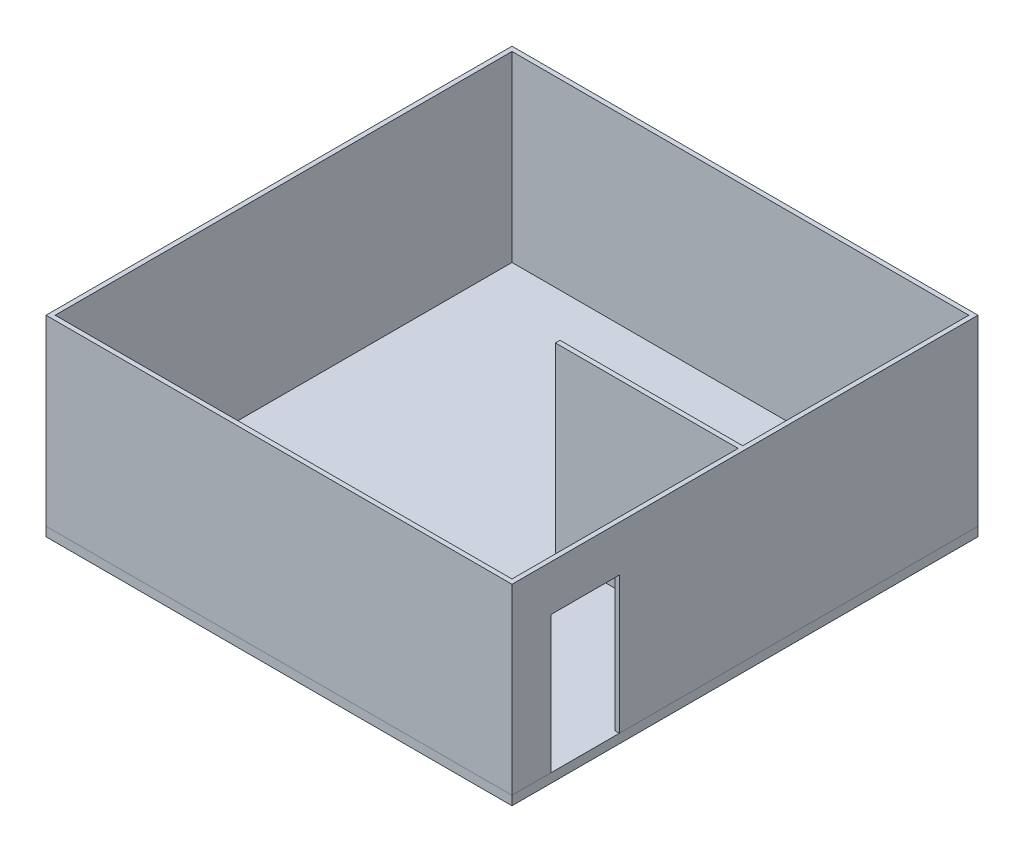
SolidWorks part; units mm, degrees
ref_plane "Front Plane" through (0, 0, 0) normal (0, 0, 1) x (1, 0, 0)
ref_plane "Top Plane" through (0, 0, 0) normal (0, 1, 0) x (1, 0, 0)
ref_plane "Right Plane" through (0, 0, 0) normal (1, 0, 0) x (0, 0, -1)
sketch "Sketch1" plane through (0, 0, 0) normal (0, 1, 0) x (1, 0, 0)
  line L0 (-5100, 5100) -> (-5100, -5100)
  line L1 (-5000, 5000) -> (5000, 5000)
  line L2 (-5000, 5000) -> (-5000, -5000)
  line L3 (-5000, -5000) -> (5000, -5000)
  line L4 (5000, 5000) -> (5000, -5000)
  line L5 (-5000, 5000) -> (5000, -5000) construction
  line L6 (-5000, -5000) -> (5000, 5000) construction
  line L7 (-5100, -5100) -> (5100, -5100)
  line L8 (5100, 5100) -> (5100, -5100)
  line L9 (-5100, 5100) -> (5100, 5100)
  line L11 (5000, 50) -> (1000, 50)
  line L12 (5000, 50) -> (5000, -50)
  line L13 (5000, -50) -> (1000, -50)
  line L14 (1000, 50) -> (1000, -50)
  point P0 (0, 0)
  point P14 (1000, 0)
  dimension "D1" = 10000
  dimension "D2" = 10000
  dimension "D4" = 100
  dimension "D5" = 4000
  dimension "D3" = 100
extrude "Boss-Extrude1" add sketch "Sketch1" along normal blind 4000 contours L9 L0 L7 L8 L1 L4 L3 L2 | L11 L14 L13 L4
sketch "Sketch2" plane through (0, 0, 0) normal (0, -1, 0) x (1, 0, 0)
  line L1 (-5100, 5100) -> (5100, 5100)
  line L2 (-5100, 5100) -> (-5100, -5100)
  line L3 (-5100, -5100) -> (5100, -5100)
  line L4 (5100, 5100) -> (5100, -5100)
  line L5 (-5100, 5100) -> (5100, -5100) construction
  line L6 (-5100, -5100) -> (5100, 5100) construction
  point P0 (0, 0)
extrude "Boss-Extrude2" add sketch "Sketch2" along normal blind 200 separate body
sketch "Sketch3" plane through (5100, 0, 0) normal (1, 0, 0) x (0, 0, -1)
  line L0 (5100, 0) -> (-5100, 0) construction
  line L1 (-4250, 0) -> (-2750, 0)
  line L2 (-4250, 0) -> (-4250, 3000)
  line L3 (-4250, 3000) -> (-2750, 3000)
  line L4 (-2750, 0) -> (-2750, 3000)
  point P6 (-3500, 3000)
  dimension "D1" = 1500
  dimension "D2" = 3000
  dimension "D3" = 3500
extrude "Cut-Extrude1" cut sketch "Sketch3" against normal up to next (100 mm away)
